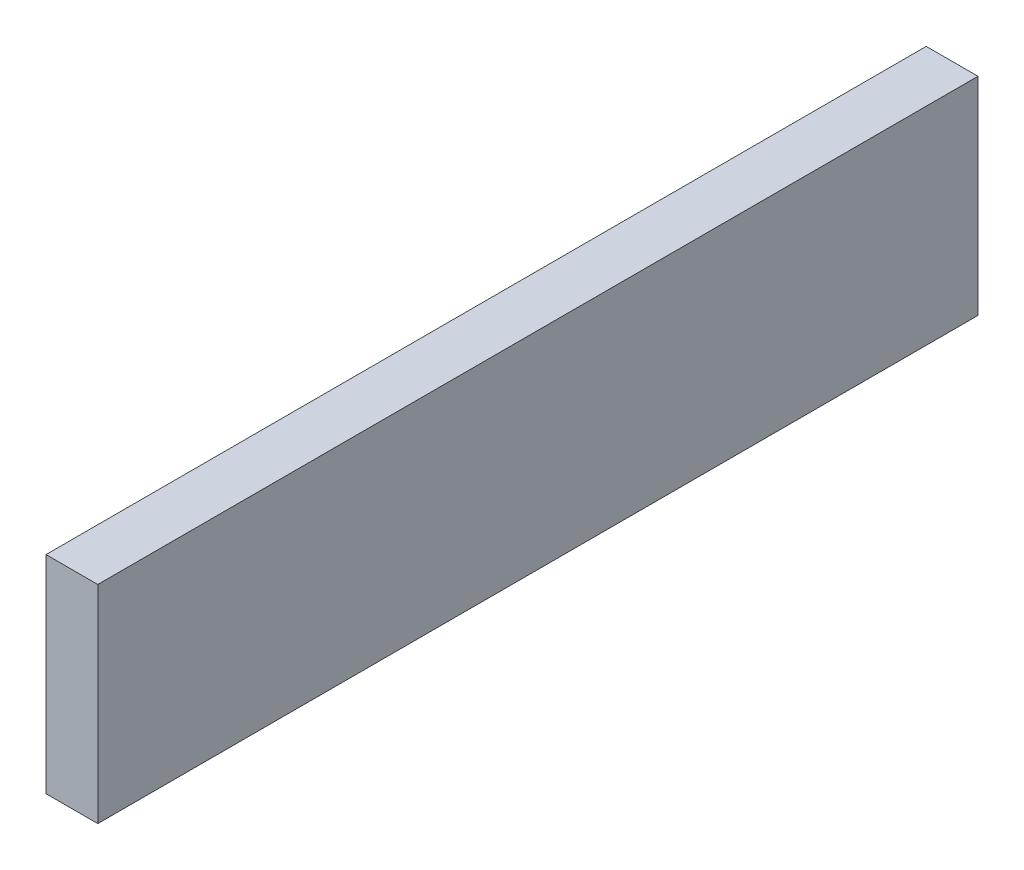
SolidWorks part; units mm, degrees
ref_plane "Alzado" through (0, 0, 0) normal (0, 0, 1) x (1, 0, 0)
ref_plane "Planta" through (0, 0, 0) normal (0, 1, 0) x (1, 0, 0)
ref_plane "Vista lateral" through (0, 0, 0) normal (1, 0, 0) x (0, 0, -1)
sketch "Croquis1" plane through (0, 0, 0) normal (1, 0, 0) x (0, 0, -1)
  line L1 (-85, -20) -> (85, -20)
  line L2 (-85, -20) -> (-85, 20)
  line L3 (-85, 20) -> (85, 20)
  line L4 (85, -20) -> (85, 20)
  line L5 (-85, -20) -> (85, 20) construction
  line L6 (-85, 20) -> (85, -20) construction
  point P0 (0, 0)
  dimension "D1" = 170
  dimension "D2" = 40
extrude "Saliente-Extruir1" add sketch "Croquis1" along normal mid plane 10
sketch "Croquis2" plane through (0, 0, 0) normal (1, 0, 0) x (0, 0, -1)
  line L0 (0, 20) -> (0, -20) construction
  line L1 (85, 20) -> (-85, 20) construction
  line L2 (-85, -20) -> (85, -20) construction
  line L3 (-80, 20) -> (-80, -20) construction
  line L4 (-85, 15) -> (85, 15) construction
  line L5 (-85, 20) -> (-85, -20) construction
  line L6 (85, -20) -> (85, 20) construction
  line L7 (-85, 0) -> (85, 0) construction
  line L8 (-85, -15) -> (85, -15) construction
  line L9 (80, 20) -> (80, -20) construction
  circle A0 centre (-80, 15) radius 2.5
  circle A1 centre (-40, 15) radius 2.5
  circle A2 centre (0, 15) radius 2.5
  circle A3 centre (40, 15) radius 2.5
  circle A4 centre (80, 15) radius 2.5
  circle A5 centre (80, -15) radius 2.5
  circle A6 centre (40, -15) radius 2.5
  circle A7 centre (0, -15) radius 2.5
  circle A8 centre (-40, -15) radius 2.5
  circle A9 centre (-80, -15) radius 2.5
  dimension "D3" = 5
  dimension "D1" = 5
  dimension "D2" = 5
  dimension "D4" = 5
extrude "Cortar-Extruir1" cut sketch "Croquis2" against normal blind 5
sketch "Croquis3" plane through (0, 0, -85) normal (0, 0, -1) x (-1, 0, 0)
  line L0 (0, 20) -> (0, -20) construction
  line L1 (-5, 20) -> (5, 20) construction
  line L2 (-5, -20) -> (5, -20) construction
  line L3 (-5, 0) -> (5, 0) construction
  line L4 (-5, -20) -> (-5, 20) construction
  line L5 (5, -20) -> (5, 20) construction
  line L6 (-5, 15) -> (5, 15) construction
  circle A0 centre (0, 15) radius 2.7483
  circle A1 centre (0, -15) radius 2.7483
  circle A2 centre (0, 0) radius 2.7483
  dimension "D1" = 5
  dimension "D2" = 2
extrude "Cortar-Extruir2" cut sketch "Croquis3" against normal blind 5
